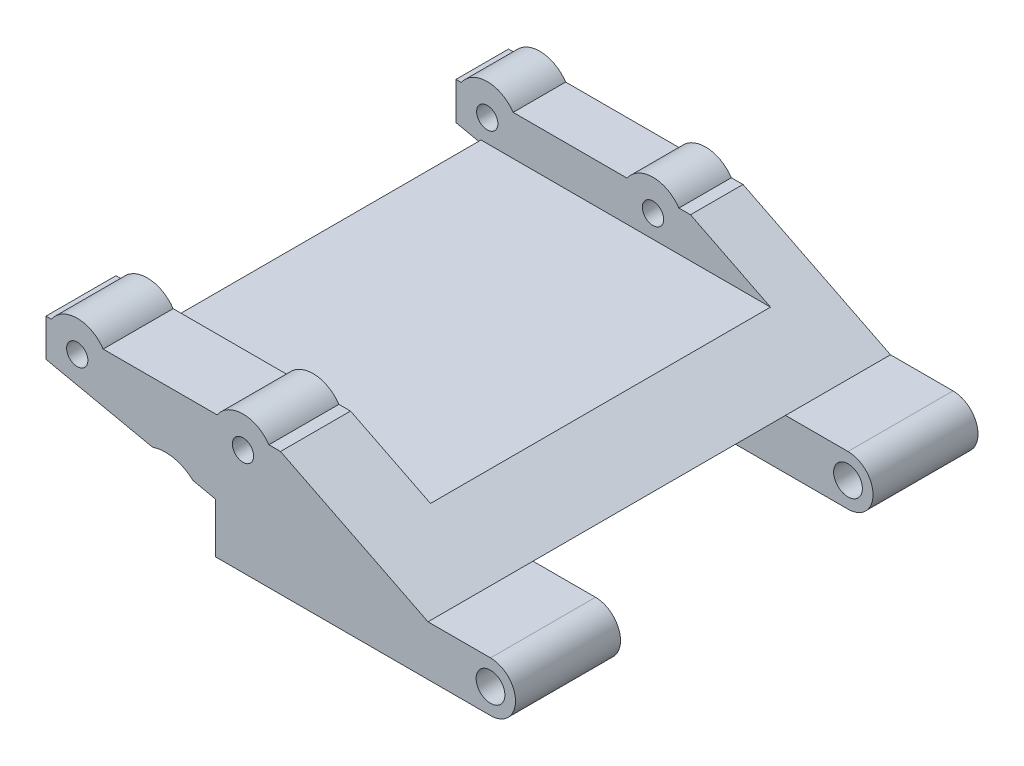
SolidWorks part; units mm, degrees
ref_plane "前视基准面" through (0, 0, 0) normal (0, 0, 1) x (1, 0, 0)
ref_plane "上视基准面" through (0, 0, 0) normal (0, 1, 0) x (1, 0, 0)
ref_plane "右视基准面" through (0, 0, 0) normal (1, 0, 0) x (0, 0, -1)
other "Configuration Table"
sketch "草图1" plane through (0, 0, 0) normal (0, 0, 1) x (1, 0, 0)
  line L0 (0, 0) -> (0, -50000) construction
  line L5 (-13, 2) -> (13, 2)
  line L6 (-13, 2) -> (-13, -2)
  line L7 (-13, -2) -> (13, -2)
  line L8 (13, 2) -> (13, -2)
  line L9 (-13, 2) -> (13, -2) construction
  line L10 (-13, -2) -> (13, 2) construction
  circle A0 centre (13, 0) radius 2
  circle A1 centre (13, 0) radius 1.15
  circle A2 centre (-13, 0) radius 2
  circle A3 centre (-13, 0) radius 1.15
  point P0 (0, 0)
  dimension "D1" = 2.3
  dimension "D2" = 4
  dimension "D3" = 26
extrude "凸台-拉伸1" add sketch "草图1" along normal mid plane 37 contours L6 A3 A2 | L6 A3 A2 | L5 A2 L7 A0 | A1 L8 A0 | A1 L8 A0
sketch "草图2" plane through (0, 2, 0) normal (0, 1, 0) x (1, 0, 0)
  line L0 (0, 0) -> (50000, 0) construction
  line L1 (-15, 18.5) -> (-15, -18.5) construction
  line L2 (-9, 2.9) -> (-15, 2.9)
  line L3 (-9, 2.9) -> (-9, -2.9)
  line L4 (-9, -2.9) -> (-15, -2.9)
  line L5 (-15, 2.9) -> (-15, -2.9)
  line L6 (-9, 2.9) -> (-15, -2.9) construction
  line L7 (-9, -2.9) -> (-15, 2.9) construction
  line L8 (-9, -18.5) -> (-15, -18.5)
  line L9 (-9, 9.1) -> (-15, 9.1)
  line L10 (-9, 9.1) -> (-9, 18.5)
  line L11 (-9, 18.5) -> (-15, 18.5)
  line L12 (-15, 9.1) -> (-15, 18.5)
  line L13 (-9, 9.1) -> (-15, 18.5) construction
  line L14 (-9, 18.5) -> (-15, 9.1) construction
  line L15 (-15, -9.1) -> (-15, -18.5)
  line L16 (-9, -9.1) -> (-15, -9.1)
  line L17 (-9, -9.1) -> (-9, -18.5)
  line L18 (15, -18.5) -> (15, 18.5) construction
  line L19 (3, 10.1) -> (15, 10.1)
  line L20 (3, 10.1) -> (3, -10.1)
  line L21 (3, -10.1) -> (15, -10.1)
  line L22 (15, 10.1) -> (15, -10.1)
  line L23 (3, 10.1) -> (15, -10.1) construction
  line L24 (3, -10.1) -> (15, 10.1) construction
  point P3 (-12, 0)
  point P10 (-12, 13.8)
  point P20 (9, 0)
  dimension "D1" = 5.8
  dimension "D2" = 6
  dimension "D3" = 9.4
  dimension "D4" = 12
  dimension "D5" = 20.2
extrude "切除-拉伸1" cut sketch "草图2" against normal through all
sketch "草图4" plane through (0, 0, 18.5) normal (0, 0, 1) x (1, 0, 0)
  line L0 (0, 0) -> (-50000, 0) construction
  line L1 (-9, -2) -> (-9, 2) construction
  line L2 (-9, 2) -> (-22.56, 4.9)
  line L3 (-22.56, 4.9) -> (-22.56, 7.9)
  line L4 (-22.56, 7.9) -> (-3.8, 7.9)
  line L5 (-3.8, 7.9) -> (8, 2)
  line L6 (-9, 2) -> (13, 2) construction
  circle A0 centre (-6.8, 6.5) radius 0.85
  circle A1 centre (-20.06, 6.5) radius 0.85
  circle A2 centre (13, 0) radius 1.15 construction
  circle A3 centre (-20.06, 6.5) radius 2.5
  circle A4 centre (-6.8, 6.5) radius 2.5
  circle A5 centre (-13, 0) radius 3.25
  line M13 (13, 2) -> (-9, 2)
  dimension "D1" = 13.26
  dimension "D2" = 6.5
  dimension "D3" = 1.7
  dimension "D6" = 5
  dimension "D11" = 6.5
  dimension "D4" = 2.2
  dimension "D5" = 5
  dimension "D7" = 1.4
  dimension "D8" = 2.5
  dimension "D9" = 3
  dimension "D10" = 3
extrude "凸台-拉伸2" add sketch "草图4" against normal up to surface (37 mm away) contours A3 L3 L2 | A3 L4 L3 | L4 A3 L2 A1 | A4 L4 A3 L2 L5 M13 | L4 A3 | L4 A4 A0 | L4 A4
sketch "草图5" plane through (-22.56, 0, 0) normal (-1, 0, 0) x (0, 0, 1)
  line L0 (18.5, 9) -> (-18.5, 9) construction
  line L1 (-14.3, 4.7) -> (12.9, 4.7)
  line L2 (-14.3, 4.7) -> (-14.3, 9)
  line L3 (-14.3, 9) -> (12.9, 9)
  line L4 (12.9, 4.7) -> (12.9, 9)
  line L5 (-14.3, 4.7) -> (12.9, 9) construction
  line L6 (-14.3, 9) -> (12.9, 4.7) construction
  line L7 (18.5, 4.9) -> (18.5, 7.9) construction
  line L8 (-18.5, 7.9) -> (-18.5, 4.9) construction
  point P0 (-0.7, 6.85)
  dimension "D1" = 5.6
  dimension "D2" = 4.2
  dimension "D3" = 4.3
extrude "切除-拉伸2" cut sketch "草图5" against normal through all
sketch "草图6" plane through (-22.56, 0, 0) normal (-1, 0, 0) x (0, 0, 1)
  line L0 (12.9, 4.7) -> (-14.3, 4.7) construction
  line L1 (-14.3, 4.45) -> (12.9, 4.45)
  line L2 (-14.3, 4.45) -> (-14.3, 4.95)
  line L3 (-14.3, 4.95) -> (12.9, 4.95)
  line L4 (12.9, 4.45) -> (12.9, 4.95)
  line L5 (-14.3, 4.45) -> (12.9, 4.95) construction
  line L6 (-14.3, 4.95) -> (12.9, 4.45) construction
  line L7 (12.9, 4.9) -> (12.9, 7.9) construction
  point P0 (-0.7, 4.7)
  dimension "D1" = 0.5
extrude "切除-拉伸3" cut sketch "草图6" against normal blind 2
